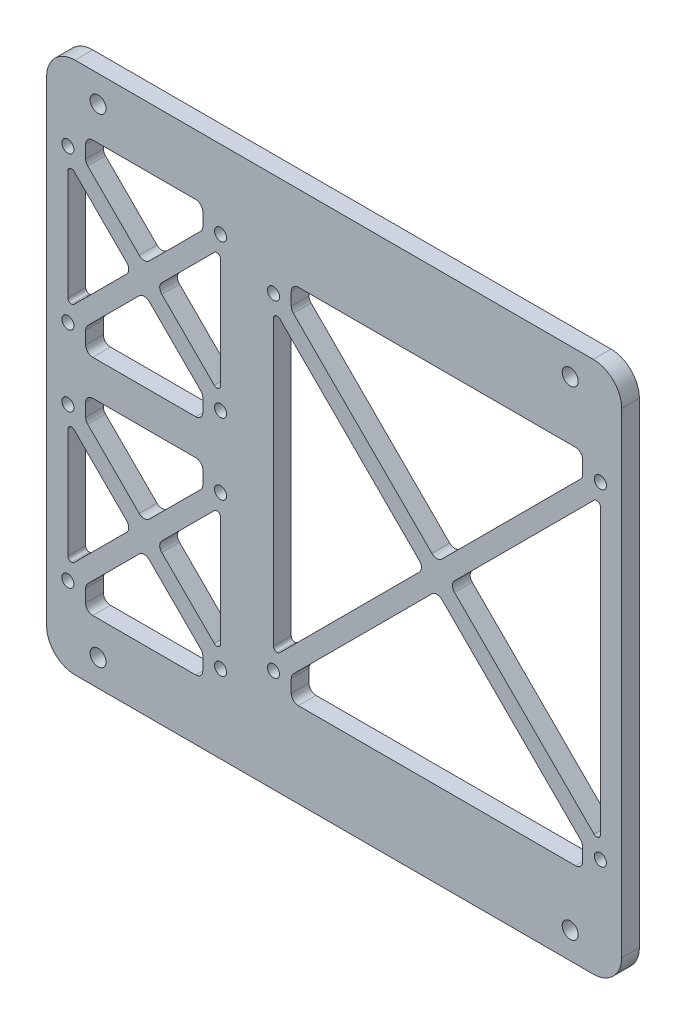
SolidWorks part; units mm, degrees
other "ﾏｰｸｱｯﾌﾟ1"
sketch "ｽｹｯﾁ7" plane through (-180, 0, 5) normal (-0.3478, -0.355, 0.8677) x (-0.0666, -0.9138, -0.4006)
material "MDF"
ref_plane "正面" through (0, 0, 0) normal (1, 0, 0) x (0, 1, 0)
ref_plane "平面" through (0, 0, 0) normal (0, 0, 1) x (0, 1, 0)
ref_plane "右側面" through (0, 0, 0) normal (0, 1, 0) x (-1, 0, 0)
sketch "ｽｹｯﾁ1" plane through (0, 0, 0) normal (0, 0, 1) x (0, 1, 0)
  line L1 (0, 0) -> (150, 0)
  line L3 (0, 162) -> (150, 162)
  line L4 (150, 0) -> (150, 162)
  line L10 (0, 0) -> (0, 162)
  dimension "D1" = 150
  dimension "D2" = 162
extrude "ﾎﾞｽ - 押し出し1" add sketch "ｽｹｯﾁ1" along normal blind 5
sketch "ｽｹｯﾁ2" plane through (0, 0, 5) normal (0, 0, 1) x (1, 0, 0)
  line L1 (0, 0) -> (0, 150) construction
  line L2 (-162, 150) -> (-162, 0) construction
  line L3 (-162, 150) -> (-162, 0) construction
  point P8 (-6, 121.04)
  point P9 (-6, 28.96)
  point P10 (-98.08, 28.96)
  point P11 (-113, 128)
  point P16 (-98.08, 121.04)
  point P17 (-156, 85)
  point P18 (-113, 85)
  point P22 (-156, 128)
  point P23 (-113, 65)
  point P24 (-156, 22)
  point P26 (-113, 22)
  point P27 (-156, 65)
  point P32 (0, 75)
  point P38 (-162, 75)
  dimension "D2" = 6
  dimension "D5" = 92.08
  dimension "D6" = 92.08
  dimension "D7" = 43
  dimension "D8" = 43
  dimension "D9" = 43
  dimension "D10" = 43
  dimension "D11" = 46.04
  dimension "D12" = 6
  dimension "D14" = 10
  dimension "D15" = 10
hole_wizard "M3 すきま穴1" positions "ｽｹｯﾁ2" profile "ｽｹｯﾁ3" hole size "M3" standard "JIS" end condition through all
sketch "ｽｹｯﾁ3" plane through (-156, 65, 5) normal (1, 0, 0) x (0, -1, 0)
  line L0 (0, 0) -> (0, 5)
  line L1 (0, 5) -> (1.7, 5)
  line L2 (1.7, 5) -> (1.7, 0)
  line L5 (1.7, 0) -> (0, 0)
  line L11 (0, -6.35) -> (0, 107.95) construction
  dimension "通し穴の直径" = 3.4
  dimension "通し穴の深さ" = 5
hole_wizard "M4 すきま穴1" positions "ｽｹｯﾁ8" profile "ｽｹｯﾁ9" hole size "M4" standard "JIS" end condition through all
sketch "ｽｹｯﾁ8" plane through (0, 0, 5) normal (0, 0, 1) x (1, 0, 0)
  line L0 (0, 150) -> (-162, 150) construction
  line L1 (-162, 0) -> (0, 0) construction
  point P0 (-147.5, 142.5)
  point P2 (-14.5, 142.5)
  point P4 (-14.5, 7.5)
  point P6 (-147.5, 7.5)
  point P11 (-81, 150)
  dimension "D1" = 133
  dimension "D2" = 66.5
  dimension "D3" = 7.5
  dimension "D4" = 7.5
sketch "ｽｹｯﾁ9" plane through (-147.5, 142.5, 5) normal (1, 0, 0) x (0, -1, 0)
  line L0 (0, 0) -> (0, 5)
  line L1 (0, 5) -> (2.25, 5)
  line L2 (2.25, 5) -> (2.25, 0)
  line L5 (2.25, 0) -> (0, 0)
  line L11 (0, -6.35) -> (0, 107.95) construction
  dimension "通し穴の直径" = 4.5
  dimension "通し穴の深さ" = 5
sketch "ｽｹｯﾁ6" plane through (0, 0, 5) normal (0, 0, 1) x (1, 0, 0)
  line L1 (-98.08, 28.96) -> (-6, 28.96) construction
  line L2 (-98.08, 28.96) -> (-98.08, 121.04) construction
  line L3 (-98.08, 121.04) -> (-6, 121.04) construction
  line L4 (-6, 28.96) -> (-6, 121.04) construction
  line L5 (-156, 85) -> (-113, 85) construction
  line L6 (-156, 85) -> (-156, 128) construction
  line L7 (-156, 128) -> (-113, 128) construction
  line L8 (-113, 85) -> (-113, 128) construction
  line L9 (-156, 22) -> (-113, 22) construction
  line L10 (-156, 22) -> (-156, 65) construction
  line L11 (-156, 65) -> (-113, 65) construction
  line L12 (-113, 22) -> (-113, 65) construction
  line L20 (-93.08, 23.96) -> (-93.08, 30.4245)
  line L21 (-98.08, 116.04) -> (-96.6155, 116.04)
  line L22 (-11, 23.96) -> (-11, 30.4245)
  line L23 (-98.08, 33.96) -> (-96.6155, 33.96)
  line L25 (-93.08, 126.04) -> (-11, 126.04)
  line L27 (-93.08, 23.96) -> (-11, 23.96)
  line L28 (-151, 133) -> (-118, 133)
  line L32 (-151, 70) -> (-118, 70)
  line L34 (-151, 17) -> (-118, 17)
  line L36 (-156, 65) -> (-113, 22) construction
  line L37 (-156, 22) -> (-113, 65) construction
  line L38 (-156, 128) -> (-113, 85) construction
  line L39 (-156, 85) -> (-113, 128) construction
  line L40 (-98.08, 121.04) -> (-6, 28.96) construction
  line L41 (-98.08, 28.96) -> (-6, 121.04) construction
  line L42 (-154.5355, 123) -> (-138.0355, 106.5)
  line L43 (-151, 86.4645) -> (-134.5, 102.9645)
  line L44 (-151, 23.4645) -> (-134.5, 39.9645)
  line L45 (-154.5355, 60) -> (-138.0355, 43.5)
  line L46 (-93.08, 30.4245) -> (-52.04, 71.4645)
  line L47 (-96.6155, 116.04) -> (-55.5755, 75)
  line L48 (-151, 126.5355) -> (-134.5, 110.0355)
  line L49 (-154.5355, 90) -> (-138.0355, 106.5)
  line L50 (-154.5355, 27) -> (-138.0355, 43.5)
  line L51 (-151, 63.5355) -> (-134.5, 47.0355)
  line L52 (-96.6155, 33.96) -> (-55.5755, 75)
  line L53 (-93.08, 119.5755) -> (-52.04, 78.5355)
  line L54 (-154.2322, 129.7678) -> (-111.2322, 86.7678) construction
  line L55 (-157.7678, 126.2322) -> (-114.7678, 83.2322) construction
  line L56 (-157.7678, 86.7678) -> (-114.7678, 129.7678) construction
  line L57 (-154.2322, 83.2322) -> (-111.2322, 126.2322) construction
  line L58 (-157.7678, 23.7678) -> (-114.7678, 66.7678) construction
  line L59 (-154.2322, 20.2322) -> (-111.2322, 63.2322) construction
  line L60 (-154.2322, 66.7678) -> (-111.2322, 23.7678) construction
  line L61 (-157.7678, 63.2322) -> (-114.7678, 20.2322) construction
  line L62 (-99.8478, 30.7278) -> (-7.7678, 122.8078) construction
  line L63 (-96.3122, 27.1922) -> (-4.2322, 119.2722) construction
  line L64 (-118, 133) -> (-118, 126.5355)
  line L65 (-114.4645, 123) -> (-113, 123)
  line L66 (-114.4645, 90) -> (-113, 90)
  line L67 (-118, 86.4645) -> (-118, 80)
  line L68 (-151, 80) -> (-151, 86.4645)
  line L69 (-156, 90) -> (-154.5355, 90)
  line L71 (-156, 123) -> (-154.5355, 123)
  line L72 (-151, 133) -> (-151, 126.5355)
  line L74 (-161, 133) -> (-108, 133) construction
  line L75 (-161, 80) -> (-161, 133) construction
  line L76 (-108, 80) -> (-108, 133) construction
  line L77 (-151, 80) -> (-118, 80)
  line L78 (-161, 80) -> (-108, 80) construction
  line L79 (-156, 123) -> (-156, 90)
  line L80 (-134.5, 110.0355) -> (-118, 126.5355)
  line L81 (-134.5, 102.9645) -> (-118, 86.4645)
  line L82 (-130.9645, 106.5) -> (-114.4645, 123)
  line L83 (-130.9645, 106.5) -> (-114.4645, 90)
  line L84 (-134.5, 39.9645) -> (-118, 23.4645)
  line L85 (-161, 70) -> (-108, 70) construction
  line L86 (-161, 17) -> (-161, 70) construction
  line L87 (-108, 17) -> (-108, 70) construction
  line L88 (-161, 17) -> (-108, 17) construction
  line L89 (-130.9645, 43.5) -> (-114.4645, 60)
  line L90 (-130.9645, 43.5) -> (-114.4645, 27)
  line L91 (-134.5, 47.0355) -> (-118, 63.5355)
  line L92 (-151, 63.5355) -> (-151, 70)
  line L93 (-156, 60) -> (-156, 27)
  line L94 (-118, 63.5355) -> (-118, 70)
  line L95 (-114.4645, 60) -> (-113, 60)
  line L96 (-114.4645, 27) -> (-113, 27)
  line L97 (-118, 23.4645) -> (-118, 17)
  line L98 (-151, 23.4645) -> (-151, 17)
  line L99 (-93.08, 33.96) -> (-93.08, 116.04) construction
  line L100 (-93.08, 116.04) -> (-11, 116.04) construction
  line L101 (-11, 33.96) -> (-11, 116.04) construction
  line L102 (-93.08, 33.96) -> (-11, 33.96) construction
  line L104 (-93.08, 119.5755) -> (-93.08, 126.04)
  line L105 (-103.08, 23.96) -> (-103.08, 126.04) construction
  line L106 (-103.08, 23.96) -> (-1, 23.96) construction
  line L107 (-7.4645, 33.96) -> (-6, 33.96)
  line L108 (-11, 119.5755) -> (-11, 126.04)
  line L109 (-1, 23.96) -> (-1, 126.04) construction
  line L110 (-96.3122, 122.8078) -> (-4.2322, 30.7278) construction
  line L111 (-7.4645, 116.04) -> (-6, 116.04)
  line L112 (-99.8478, 119.2722) -> (-7.7678, 27.1922) construction
  line L113 (-103.08, 126.04) -> (-1, 126.04) construction
  line L114 (-52.04, 71.4645) -> (-11, 30.4245)
  line L115 (-48.5045, 75) -> (-7.4645, 116.04)
  line L116 (-48.5045, 75) -> (-7.4645, 33.96)
  line L117 (-52.04, 78.5355) -> (-11, 119.5755)
  line L118 (-154.5355, 27) -> (-156, 27)
  line L119 (-6, 116.04) -> (-6, 33.96)
  line L120 (-154.5355, 60) -> (-156, 60)
  line L121 (-98.08, 116.04) -> (-98.08, 33.96)
  line L122 (-113, 123) -> (-113, 90)
  line L123 (-113, 60) -> (-113, 27)
  point P18 (-151, 27)
  point P19 (-151, 60)
  point P20 (-118, 60)
  point P21 (-118, 27)
  point P22 (-151, 123)
  point P23 (-118, 123)
  point P24 (-118, 90)
  point P25 (-151, 90)
  dimension "D2" = 33
  dimension "D10" = 5
  dimension "D3" = 5
  dimension "D4" = 5
  dimension "D5" = 5
  dimension "D6" = 5
  dimension "D7" = 2.5
  dimension "D8" = 2.5
extrude "ｶｯﾄ - 押し出し2" cut sketch "ｽｹｯﾁ6" against normal through all
fillet "ﾌｨﾚｯﾄ8" radius 8 4 edges at (-162, 150, 2.5) (0, 150, 2.5) (-162, 0, 2.5) (0, 0, 2.5)
fillet "ﾌｨﾚｯﾄ11" radius 2 36 edges at (-130.9645, 106.5, 2.5) (-151, 86.4645, 2.5) (-134.5, 102.9645, 2.5) (-118, 86.4645, 2.5) (-118, 80, 2.5) (-151, 80, 2.5) (-138.0355, 106.5, 2.5) (-151, 126.5355, 2.5) (-134.5, 110.0355, 2.5) (-118, 126.5355, 2.5) (-118, 133, 2.5) (-151, 133, 2.5) (-11, 119.5755, 2.5) (-11, 126.04, 2.5) (-93.08, 126.04, 2.5) (-93.08, 119.5755, 2.5) (-55.5755, 75, 2.5) (-52.04, 78.5355, 2.5) (-48.5045, 75, 2.5) (-11, 30.4245, 2.5) (-11, 23.96, 2.5) (-52.04, 71.4645, 2.5) (-93.08, 30.4245, 2.5) (-93.08, 23.96, 2.5) (-118, 23.4645, 2.5) (-118, 17, 2.5) (-151, 17, 2.5) (-151, 23.4645, 2.5) (-138.0355, 43.5, 2.5) (-134.5, 39.9645, 2.5) (-130.9645, 43.5, 2.5) (-118, 70, 2.5) (-118, 63.5355, 2.5) (-134.5, 47.0355, 2.5) (-151, 63.5355, 2.5) (-151, 70, 2.5)
fillet "ﾌｨﾚｯﾄ13" radius 1 24 edges at (-98.08, 116.04, 2.5) (-96.6155, 116.04, 2.5) (-7.4645, 116.04, 2.5) (-6, 116.04, 2.5) (-6, 33.96, 2.5) (-7.4645, 33.96, 2.5) (-96.6155, 33.96, 2.5) (-98.08, 33.96, 2.5) (-154.5355, 90, 2.5) (-156, 90, 2.5) (-156, 123, 2.5) (-154.5355, 123, 2.5) (-113, 123, 2.5) (-114.4645, 123, 2.5) (-114.4645, 90, 2.5) (-113, 90, 2.5) (-113, 27, 2.5) (-114.4645, 27, 2.5) (-113, 60, 2.5) (-114.4645, 60, 2.5) (-154.5355, 60, 2.5) (-156, 60, 2.5) (-154.5355, 27, 2.5) (-156, 27, 2.5)
equation "\"D2@ｽｹｯﾁ8\"= \"D1@ｽｹｯﾁ8\" / 2"
equation "\"D4@ｽｹｯﾁ8\"= \"D3@ｽｹｯﾁ8\""
